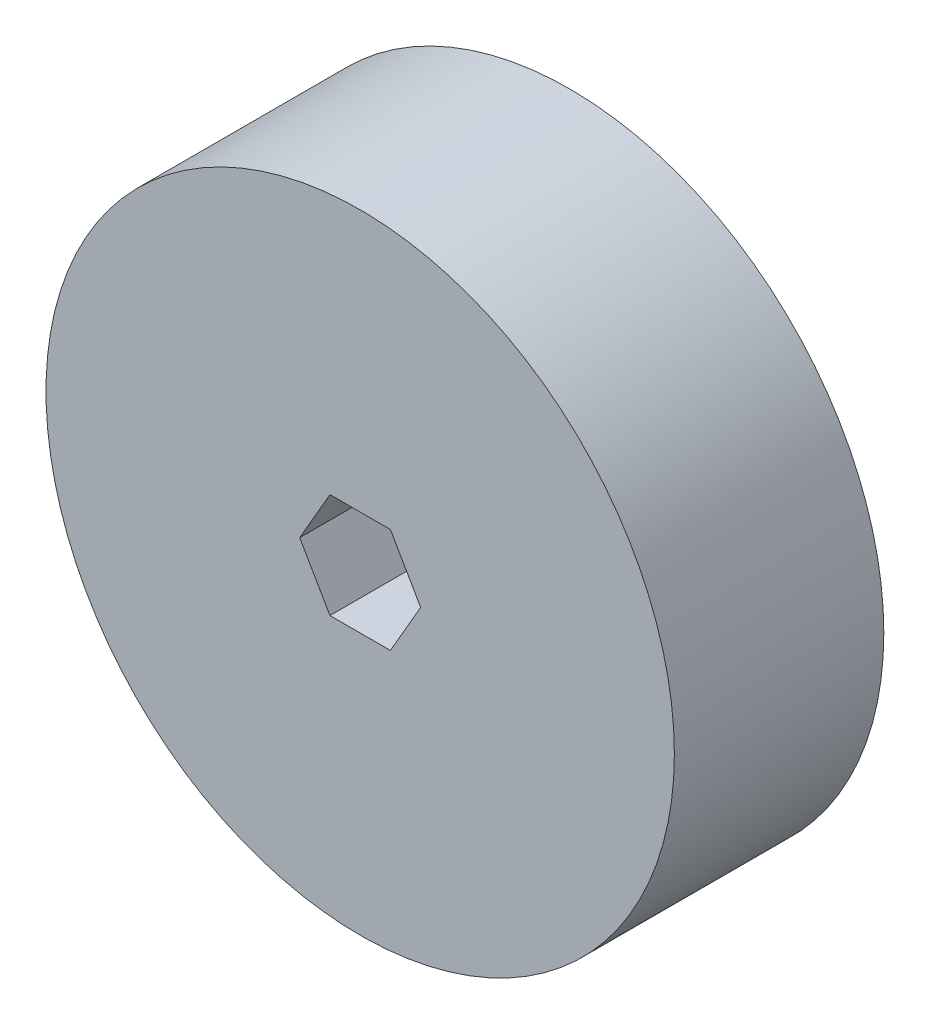
SolidWorks part; units mm, degrees
material "AISI 1020 Steel, Cold Rolled"
ref_plane "Front Plane" through (0, 0, 0) normal (0, 0, 1) x (1, 0, 0)
ref_plane "Top Plane" through (0, 0, 0) normal (0, 1, 0) x (1, 0, 0)
ref_plane "Right Plane" through (0, 0, 0) normal (1, 0, 0) x (0, 0, -1)
sketch "Sketch1" plane through (0, 0, 0) normal (0, 0, 1) x (1, 0, 0)
  line L1 (-7.3323, 0) -> (-3.6662, -6.35)
  line L2 (-3.6662, -6.35) -> (3.6662, -6.35)
  line L3 (3.6662, -6.35) -> (7.3323, 0)
  line L4 (7.3323, 0) -> (3.6662, 6.35)
  line L5 (3.6662, 6.35) -> (-3.6662, 6.35)
  line L6 (-3.6662, 6.35) -> (-7.3323, 0)
  circle A0 centre (0, 0) radius 38.1
  circle A1 centre (0, 0) radius 6.35 construction
  dimension "D1" = 12.7
  dimension "D2" = 76.2
extrude "Boss-Extrude1" add sketch "Sketch1" along normal blind 25.4
